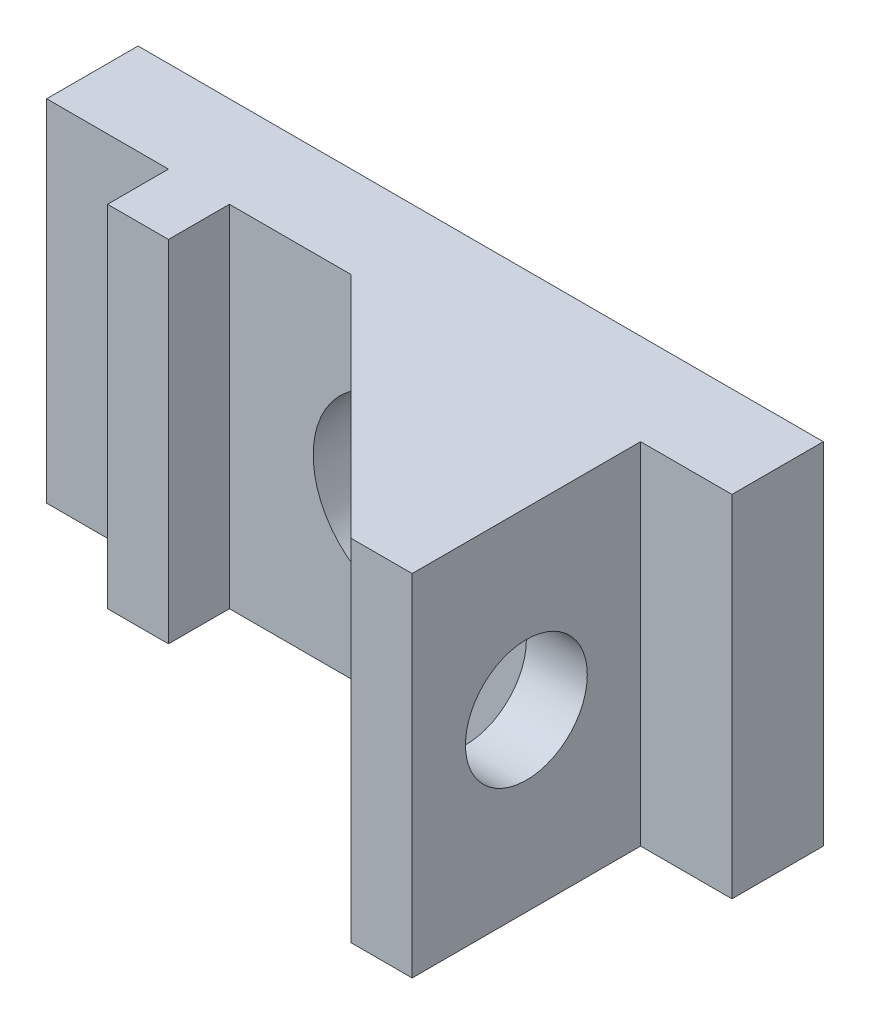
SolidWorks part; units mm, degrees
ref_plane "Спереди" through (0, 0, 0) normal (0, 0, 1) x (1, 0, 0)
ref_plane "Сверху" through (0, 0, 0) normal (0, 1, 0) x (1, 0, 0)
ref_plane "Справа" through (0, 0, 0) normal (1, 0, 0) x (0, 0, -1)
sketch "Эскиз1" plane through (0, 0, 0) normal (0, 1, 0) x (1, 0, 0)
  line L1 (-22.5, 10.5) -> (22.5, 10.5)
  line L2 (-22.5, 10.5) -> (-22.5, -10.5)
  line L3 (-22.5, -10.5) -> (22.5, -10.5)
  line L4 (22.5, 10.5) -> (22.5, -10.5)
  line L5 (-22.5, 10.5) -> (22.5, -10.5) construction
  line L6 (-22.5, -10.5) -> (22.5, 10.5) construction
  line L7 (-22.5, 10.5) -> (22.5, 10.5)
  line L8 (-22.5, 10.5) -> (-22.5, 4.5)
  line L9 (-22.5, 4.5) -> (22.5, 4.5)
  line L10 (22.5, 10.5) -> (22.5, 4.5)
  line L11 (16.5, 4.5) -> (12.5, 4.5)
  line L12 (16.5, 4.5) -> (16.5, -10.5)
  line L13 (16.5, -10.5) -> (12.5, -10.5)
  line L14 (12.5, 4.5) -> (12.5, -10.5)
  line L15 (-10.5, 4.5) -> (-14.5, 4.5)
  line L16 (-10.5, 4.5) -> (-10.5, 0.5)
  line L17 (-10.5, 0.5) -> (-14.5, 0.5)
  line L18 (-14.5, 4.5) -> (-14.5, 0.5)
  point P0 (0, 0)
  dimension "D1" = 45
  dimension "D2" = 21
  dimension "D3" = 6
  dimension "D4" = 4
  dimension "D5" = 6
  dimension "D6" = 4
  dimension "D7" = 8
  dimension "D8" = 4
extrude "Бобышка-Вытянуть1" add sketch "Эскиз1" along normal blind 23 contours L2 L9 L4 L1 | L9 L18 L17 L16 | L9 L14 L3 L12
sketch "Эскиз2" plane through (0, 23, 0) normal (0, 1, 0) x (1, 0, 0)
  line L0 (12.5, -10.5) -> (-2.5, 4.5)
  line L1 (-10.5, 4.5) -> (12.5, 4.5) construction
  line L2 (12.5, -10.5) -> (12.5, 4.5)
  line L3 (12.5, 4.5) -> (-2.5, 4.5)
extrude "Бобышка-Вытянуть2" add sketch "Эскиз2" against normal blind 4
sketch "Эскиз3" plane through (0, 0, -4.5) normal (0, 0, 1) x (1, 0, 0)
  line L0 (-10.5, 11.5) -> (12.5, 11.5) construction
  line L3 (-10.5, 23) -> (-10.5, 0) construction
  line L4 (12.5, 19) -> (12.5, 0) construction
  circle A0 centre (1, 11.5) radius 6
  dimension "D1" = 12
extrude "Вырез-Вытянуть1" cut sketch "Эскиз3" against normal through all
sketch "Эскиз4" plane through (16.5, 0, 0) normal (-1, 0, 0) x (0, 0, 1)
  line L0 (-4.5, 11.5) -> (10.5, 11.5) construction
  line L2 (10.5, 19) -> (10.5, 0) construction
  line L3 (-4.5, 19) -> (-4.5, 0) construction
  line L4 (10.5, 23) -> (10.5, 0) construction
  circle A0 centre (3, 11.5) radius 4
  dimension "D1" = 8
extrude "Вырез-Вытянуть2" cut sketch "Эскиз4" along normal up to surface (4 mm away) up to face at (12.5, 9.5, 3)
